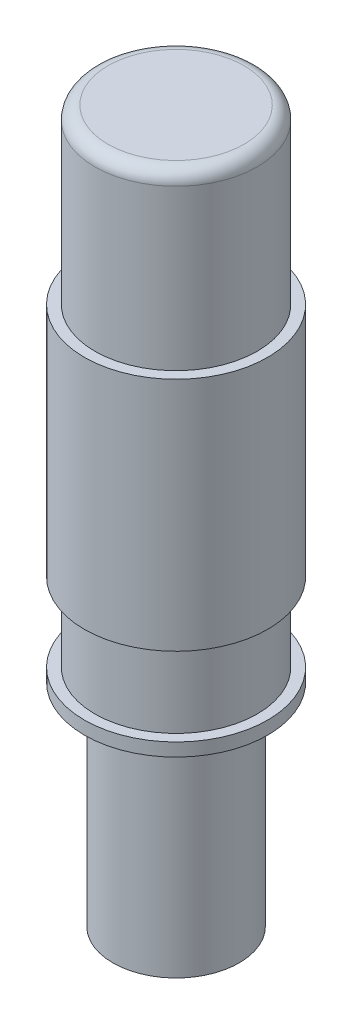
SolidWorks part; units mm, degrees
ref_plane "Front Plane" through (0, 0, 0) normal (0, 0, 1) x (1, 0, 0)
ref_plane "Top Plane" through (0, 0, 0) normal (0, 1, 0) x (1, 0, 0)
ref_plane "Right Plane" through (0, 0, 0) normal (1, 0, 0) x (0, 0, -1)
sketch "Sketch1" plane through (0, 0, 0) normal (0, 1, 0) x (1, 0, 0)
  circle A0 centre (0, 0) radius 3.5
  dimension "D1" = 7
extrude "Boss-Extrude1" add sketch "Sketch1" along normal blind 0.5
sketch "Sketch2" plane through (0, 0.5, 0) normal (0, 1, 0) x (1, 0, 0)
  circle A0 centre (0, 0) radius 3.1
  dimension "D1" = 6.2
extrude "Boss-Extrude2" add sketch "Sketch2" along normal blind 3
sketch "Sketch3" plane through (0, 3.5, 0) normal (0, 1, 0) x (1, 0, 0)
  circle A0 centre (0, 0) radius 3.5
  dimension "D1" = 7
extrude "Boss-Extrude3" add sketch "Sketch3" along normal blind 9
sketch "Sketch4" plane through (0, 12.5, 0) normal (0, 1, 0) x (1, 0, 0)
  circle A0 centre (0, 0) radius 3.1
  dimension "D1" = 6.2
extrude "Boss-Extrude4" add sketch "Sketch4" along normal blind 6.6
fillet "Fillet1" radius 0.5 1 edges at (0, 19.1, 3.1)
sketch "Sketch5" plane through (0, 0, 0) normal (0, -1, 0) x (1, 0, 0)
  line L0 (-1.4811, -1.905) -> (1.4811, -1.905)
  circle A0 centre (0, 0) radius 2.413
  dimension "D1" = 4.826
  dimension "D2" = 1.905
extrude "Boss-Extrude5" add sketch "Sketch5" along normal blind 8.0772 contours L0 A0
